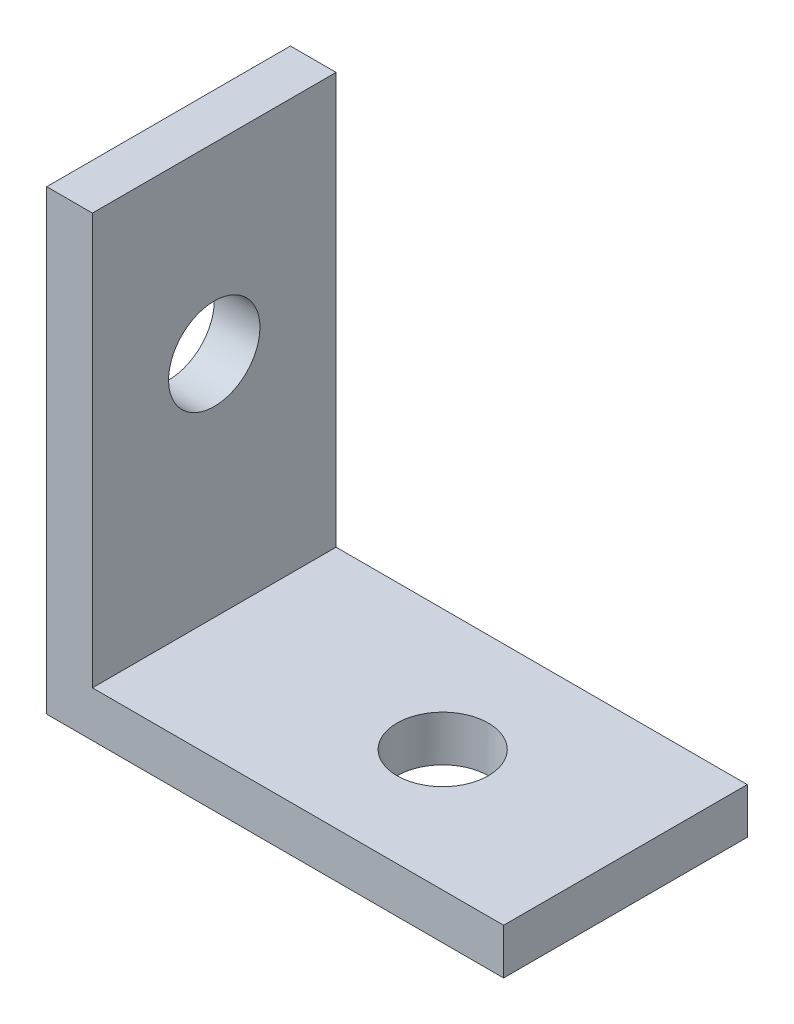
SolidWorks part; units mm, degrees
ref_plane "Plan de face" through (0, 0, 0) normal (0, 0, 1) x (1, 0, 0)
ref_plane "Plan de dessus" through (0, 0, 0) normal (0, 1, 0) x (1, 0, 0)
ref_plane "Plan de droite" through (0, 0, 0) normal (1, 0, 0) x (0, 0, -1)
sketch "Esquisse1" plane through (0, 0, 0) normal (0, 0, 1) x (1, 0, 0)
  line L0 (-3.4637, -6.0958) -> (-1.9637, -6.0958)
  line L1 (-1.9637, -6.0958) -> (-1.9637, -19.5958)
  line L2 (-1.9637, -19.5958) -> (11.5363, -19.5958)
  line L3 (11.5363, -19.5958) -> (11.5363, -21.0958)
  line L4 (11.5363, -21.0958) -> (-3.4637, -21.0958)
  line L5 (-3.4637, -21.0958) -> (-3.4637, -6.0958)
  dimension "D1" = 1.5
  dimension "D2" = 1.5
  dimension "D3" = 15
  dimension "D4" = 15
extrude "Extrusion1" add sketch "Esquisse1" along normal blind 8
sketch "Esquisse2" plane through (-1.9637, 0, 0) normal (1, 0, 0) x (0, 0, -1)
  line L0 (-8, -19.5958) -> (-8, -6.0958) construction
  line L2 (-8, -6.0958) -> (0, -6.0958) construction
  circle A0 centre (-4, -12.0958) radius 1.5
  dimension "D1" = 4
  dimension "D4" = 6
extrude "Extrusion2" cut sketch "Esquisse2" against normal blind 80
sketch "Esquisse3" plane through (0, -19.5958, 0) normal (0, 1, 0) x (-1, 0, 0)
  line L0 (-11.5363, 8) -> (1.9637, 8) construction
  line L2 (-11.5363, 8) -> (-11.5363, 0) construction
  circle A0 centre (-5.5363, 4) radius 1.5
  dimension "D1" = 4
  dimension "D4" = 6
extrude "Extrusion3" cut sketch "Esquisse3" against normal blind 80
